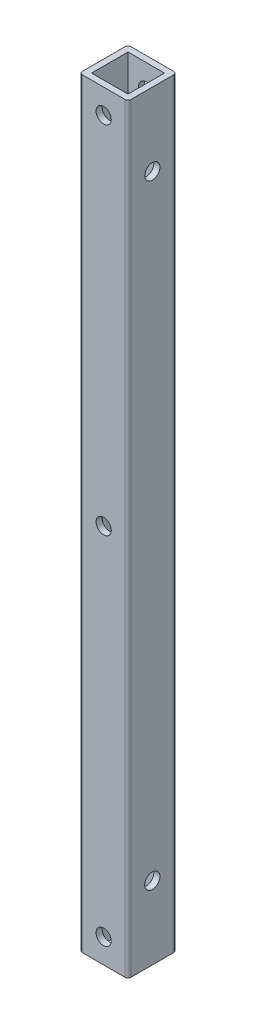
SolidWorks part; units mm, degrees
ref_plane "Front Plane" through (0, 0, 0) normal (0, 0, 1) x (1, 0, 0)
ref_plane "Top Plane" through (0, 0, 0) normal (0, 1, 0) x (1, 0, 0)
ref_plane "Right Plane" through (0, 0, 0) normal (1, 0, 0) x (0, 0, -1)
sketch "Sketch1" plane through (0, 0, 0) normal (0, 1, 0) x (1, 0, 0)
  line L0 (-6.0591, 6.2247) -> (-6.0591, -5.7753)
  line L1 (-8.0591, 8.2247) -> (7.9409, 8.2247)
  line L2 (-8.0591, 8.2247) -> (-8.0591, -7.7753)
  line L3 (-8.0591, -7.7753) -> (7.9409, -7.7753)
  line L4 (7.9409, 8.2247) -> (7.9409, -7.7753)
  line L5 (-6.0591, -5.7753) -> (5.9409, -5.7753)
  line L6 (5.9409, 6.2247) -> (5.9409, -5.7753)
  line L7 (-6.0591, 6.2247) -> (5.9409, 6.2247)
  dimension "D1" = 16
  dimension "D2" = 16
  dimension "D3" = 2
extrude "Boss-Extrude1" add sketch "Sketch1" along normal blind 250
fillet "Fillet1" radius 1 4 edges at (-8.0591, 125, 7.7753) (-8.0591, 125, -8.2247) (7.9409, 125, -8.2247) (7.9409, 125, 7.7753)
sketch "Sketch2" plane through (0, 0, 7.7753) normal (0, 0, 1) x (1, 0, 0)
  line L0 (-7.0591, 0) -> (6.9409, 0) construction
  line L1 (-8.0591, 0) -> (-8.0591, 250) construction
  circle A0 centre (-0.0591, 8) radius 2.5
  dimension "D1" = 5
  dimension "D2" = 8
  dimension "D3" = 8
extrude "Cut-Extrude1" cut sketch "Sketch2" against normal blind 16
sketch "Sketch3" plane through (0, 0, 7.7753) normal (0, 0, 1) x (1, 0, 0)
  line L0 (7.9409, 250) -> (7.9409, 0) construction
  line L1 (-7.0591, 250) -> (6.9409, 250) construction
  circle A0 centre (-0.0591, 242) radius 2.5
  dimension "D1" = 5
  dimension "D2" = 8
  dimension "D3" = 8
extrude "Cut-Extrude2" cut sketch "Sketch3" against normal blind 16
sketch "Sketch4" plane through (-8.0591, 0, 0) normal (-1, 0, 0) x (0, 0, 1)
  line L0 (-7.2247, 250) -> (6.7753, 250) construction
  line L1 (7.7753, 250) -> (7.7753, 0) construction
  line L2 (-7.2247, 0) -> (6.7753, 0) construction
  line L3 (-8.2247, 0) -> (-8.2247, 250) construction
  circle A0 centre (-0.2247, 24) radius 2.5
  circle A1 centre (-0.2247, 226) radius 2.5
  dimension "D3" = 5
  dimension "D4" = 5
  dimension "D1" = 24
  dimension "D2" = 8
  dimension "D5" = 24
  dimension "D6" = 8
extrude "Cut-Extrude3" cut sketch "Sketch4" against normal blind 16
sketch "Sketch5" plane through (0, 0, 7.7753) normal (0, 0, 1) x (1, 0, 0)
  line L0 (-8.0591, 0) -> (-8.0591, 250) construction
  line L1 (-7.0591, 250) -> (6.9409, 250) construction
  circle A0 centre (-0.0591, 125) radius 2.5
  dimension "D1" = 5
  dimension "D2" = 8
  dimension "D3" = 125
extrude "Cut-Extrude4" cut sketch "Sketch5" against normal blind 16
